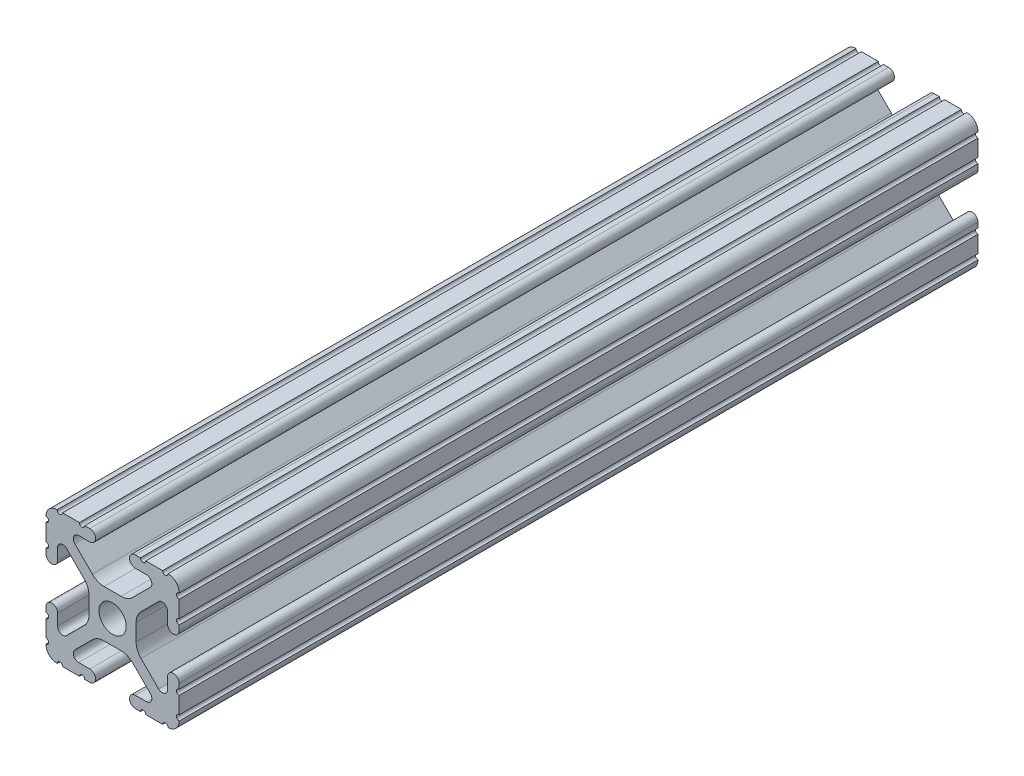
SolidWorks part; units mm, degrees
ref_plane "Front Plane" through (0, 0, 0) normal (0, 0, 1) x (1, 0, 0)
ref_plane "Top Plane" through (0, 0, 0) normal (0, 1, 0) x (1, 0, 0)
ref_plane "Right Plane" through (0, 0, 0) normal (1, 0, 0) x (0, 0, -1)
ref_plane "Plane1" through (0, 0, -25.4) normal (0, 0, -1) x (-1, 0, 0)
sketch "Sketch1" plane through (0, 0, -25.4) normal (0, 0, -1) x (-1, 0, 0)
  line L0 (12.7, -9.5504) -> (12.7, -6.3331)
  line L1 (12.7, -5.3171) -> (12.7, -4.3434)
  line L2 (10.4902, -4.3434) -> (10.4902, -6.4748)
  line L3 (8.7558, -7.1932) -> (5.4257, -3.8632)
  line L4 (4.4958, -1.6181) -> (4.4958, 1.6181)
  line L5 (5.4257, 3.8632) -> (8.7558, 7.1932)
  line L6 (10.4902, 6.4748) -> (10.4902, 4.3434)
  line L7 (12.7, 4.3434) -> (12.7, 5.3171)
  line L8 (12.7, 6.3331) -> (12.7, 9.5504)
  line L9 (9.5504, 12.7) -> (6.3331, 12.7)
  line L10 (5.3171, 12.7) -> (4.3434, 12.7)
  line L11 (4.3434, 10.4902) -> (6.4748, 10.4902)
  line L12 (7.1932, 8.7558) -> (3.8632, 5.4257)
  line L13 (1.6181, 4.4958) -> (-1.6181, 4.4958)
  line L14 (-3.8632, 5.4257) -> (-7.1932, 8.7558)
  line L15 (-6.4748, 10.4902) -> (-4.3434, 10.4902)
  line L16 (-4.3434, 12.7) -> (-5.3171, 12.7)
  line L17 (-6.3331, 12.7) -> (-9.5504, 12.7)
  line L18 (-12.7, 9.5504) -> (-12.7, 6.3331)
  line L19 (-12.7, 5.3171) -> (-12.7, 4.3434)
  line L20 (-10.4902, 4.3434) -> (-10.4902, 6.4748)
  line L21 (-8.7558, 7.1932) -> (-5.4257, 3.8632)
  line L22 (-4.4958, 1.6181) -> (-4.4958, -1.6181)
  line L23 (-5.4257, -3.8632) -> (-8.7558, -7.1932)
  line L24 (-10.4902, -6.4748) -> (-10.4902, -4.3434)
  line L25 (-12.7, -4.3434) -> (-12.7, -5.3171)
  line L26 (-12.7, -6.3331) -> (-12.7, -9.5504)
  line L27 (-9.5504, -12.7) -> (-6.3331, -12.7)
  line L28 (-5.3171, -12.7) -> (-4.3434, -12.7)
  line L29 (-4.3434, -10.4902) -> (-6.4748, -10.4902)
  line L30 (-7.1932, -8.7558) -> (-3.8632, -5.4257)
  line L31 (-1.6181, -4.4958) -> (1.6181, -4.4958)
  line L32 (3.8632, -5.4257) -> (7.1932, -8.7558)
  line L33 (6.4748, -10.4902) -> (4.3434, -10.4902)
  line L34 (4.3434, -12.7) -> (5.3171, -12.7)
  line L35 (6.3331, -12.7) -> (9.5504, -12.7)
  arc A0 (12.6998, -10.5664) -> (12.7, -9.5504) centre (12.7, -10.0584) cw
  arc A1 (12.7, -6.3331) -> (12.7, -5.3171) centre (12.7, -5.8251) cw
  arc A2 (12.7, -4.3434) -> (10.4902, -4.3434) centre (11.5951, -4.3434) ccw
  arc A3 (10.4902, -6.4748) -> (8.7558, -7.1932) centre (9.4742, -6.4748) cw
  arc A4 (5.4257, -3.8632) -> (4.4958, -1.6181) centre (7.6708, -1.6181) cw
  arc A5 (4.4958, 1.6181) -> (5.4257, 3.8632) centre (7.6708, 1.6181) cw
  arc A6 (8.7558, 7.1932) -> (10.4902, 6.4748) centre (9.4742, 6.4748) cw
  arc A7 (10.4902, 4.3434) -> (12.7, 4.3434) centre (11.5951, 4.3434) ccw
  arc A8 (12.7, 5.3171) -> (12.7, 6.3331) centre (12.7, 5.8251) cw
  arc A9 (12.7, 9.5504) -> (12.6998, 10.5664) centre (12.7, 10.0584) cw
  arc A10 (12.6998, 10.5664) -> (10.5664, 12.6998) centre (10.5918, 10.5918) ccw
  arc A11 (10.5664, 12.6998) -> (9.5504, 12.7) centre (10.0584, 12.7) cw
  arc A12 (6.3331, 12.7) -> (5.3171, 12.7) centre (5.8251, 12.7) cw
  arc A13 (4.3434, 12.7) -> (4.3434, 10.4902) centre (4.3434, 11.5951) ccw
  arc A14 (6.4748, 10.4902) -> (7.1932, 8.7558) centre (6.4748, 9.4742) cw
  arc A15 (3.8632, 5.4257) -> (1.6181, 4.4958) centre (1.6181, 7.6708) cw
  arc A16 (-1.6181, 4.4958) -> (-3.8632, 5.4257) centre (-1.6181, 7.6708) cw
  arc A17 (-7.1932, 8.7558) -> (-6.4748, 10.4902) centre (-6.4748, 9.4742) cw
  arc A18 (-4.3434, 10.4902) -> (-4.3434, 12.7) centre (-4.3434, 11.5951) ccw
  arc A19 (-5.3171, 12.7) -> (-6.3331, 12.7) centre (-5.8251, 12.7) cw
  arc A20 (-9.5504, 12.7) -> (-10.5664, 12.6998) centre (-10.0584, 12.7) cw
  arc A21 (-10.5664, 12.6998) -> (-12.6998, 10.5664) centre (-10.5918, 10.5918) ccw
  arc A22 (-12.6998, 10.5664) -> (-12.7, 9.5504) centre (-12.7, 10.0584) cw
  arc A23 (-12.7, 6.3331) -> (-12.7, 5.3171) centre (-12.7, 5.8251) cw
  arc A24 (-12.7, 4.3434) -> (-10.4902, 4.3434) centre (-11.5951, 4.3434) ccw
  arc A25 (-10.4902, 6.4748) -> (-8.7558, 7.1932) centre (-9.4742, 6.4748) cw
  arc A26 (-5.4257, 3.8632) -> (-4.4958, 1.6181) centre (-7.6708, 1.6181) cw
  arc A27 (-4.4958, -1.6181) -> (-5.4257, -3.8632) centre (-7.6708, -1.6181) cw
  arc A28 (-8.7558, -7.1932) -> (-10.4902, -6.4748) centre (-9.4742, -6.4748) cw
  arc A29 (-10.4902, -4.3434) -> (-12.7, -4.3434) centre (-11.5951, -4.3434) ccw
  arc A30 (-12.7, -5.3171) -> (-12.7, -6.3331) centre (-12.7, -5.8251) cw
  arc A31 (-12.7, -9.5504) -> (-12.6998, -10.5664) centre (-12.7, -10.0584) cw
  arc A32 (-12.6998, -10.5664) -> (-10.5664, -12.6998) centre (-10.5918, -10.5918) ccw
  arc A33 (-10.5664, -12.6998) -> (-9.5504, -12.7) centre (-10.0584, -12.7) cw
  arc A34 (-6.3331, -12.7) -> (-5.3171, -12.7) centre (-5.8251, -12.7) cw
  arc A35 (-4.3434, -12.7) -> (-4.3434, -10.4902) centre (-4.3434, -11.5951) ccw
  arc A36 (-6.4748, -10.4902) -> (-7.1932, -8.7558) centre (-6.4748, -9.4742) cw
  arc A37 (-3.8632, -5.4257) -> (-1.6181, -4.4958) centre (-1.6181, -7.6708) cw
  arc A38 (1.6181, -4.4958) -> (3.8632, -5.4257) centre (1.6181, -7.6708) cw
  arc A39 (7.1932, -8.7558) -> (6.4748, -10.4902) centre (6.4748, -9.4742) cw
  arc A40 (4.3434, -10.4902) -> (4.3434, -12.7) centre (4.3434, -11.5951) ccw
  arc A41 (5.3171, -12.7) -> (6.3331, -12.7) centre (5.8251, -12.7) cw
  arc A42 (9.5504, -12.7) -> (10.5664, -12.6998) centre (10.0584, -12.7) cw
  arc A43 (10.5664, -12.6998) -> (12.6998, -10.5664) centre (10.5918, -10.5918) ccw
  circle A44 centre (0, 0) radius 2.6035
extrude "Boss-Extrude1" add sketch "Sketch1" along normal blind 152.4
